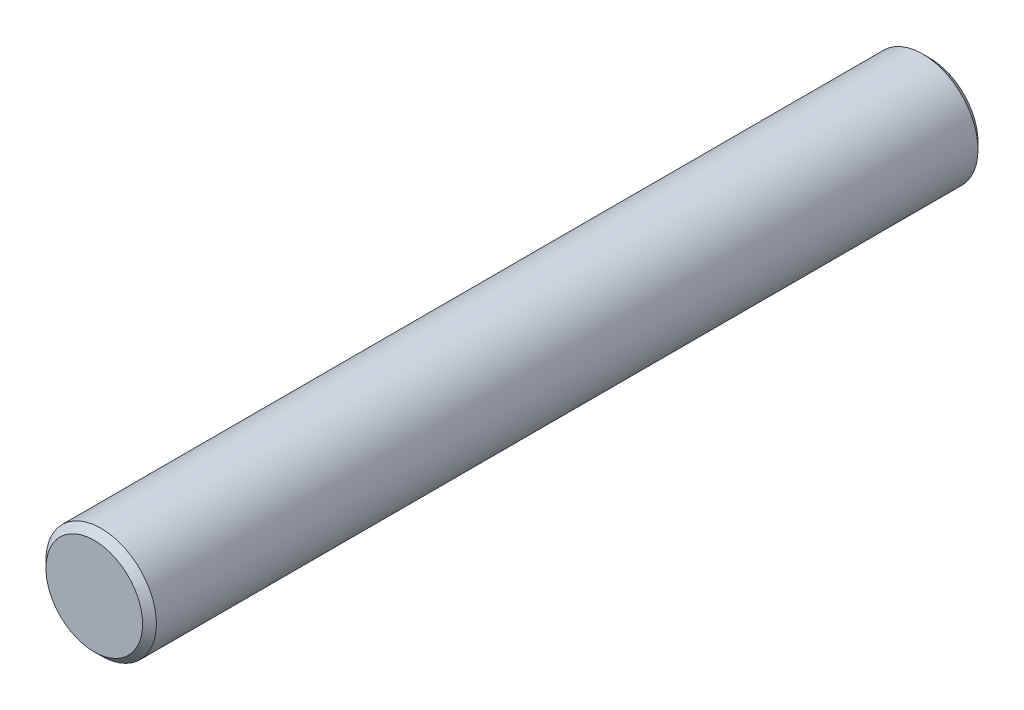
SolidWorks part; units mm, degrees
ref_plane "前视基准面" through (0, 0, 0) normal (0, 0, 1) x (1, 0, 0)
ref_plane "上视基准面" through (0, 0, 0) normal (0, 1, 0) x (1, 0, 0)
ref_plane "右视基准面" through (0, 0, 0) normal (1, 0, 0) x (0, 0, -1)
sketch "草图1" plane through (0, 0, 0) normal (0, 0, 1) x (1, 0, 0)
  circle A0 centre (0, 0) radius 8
  dimension "D1" = 16
extrude "凸台-拉伸1" add sketch "草图1" along normal blind 121
chamfer "倒角1" distance 1 angle 45 2 edges at (8, 0, 0) (8, 0, 121)
